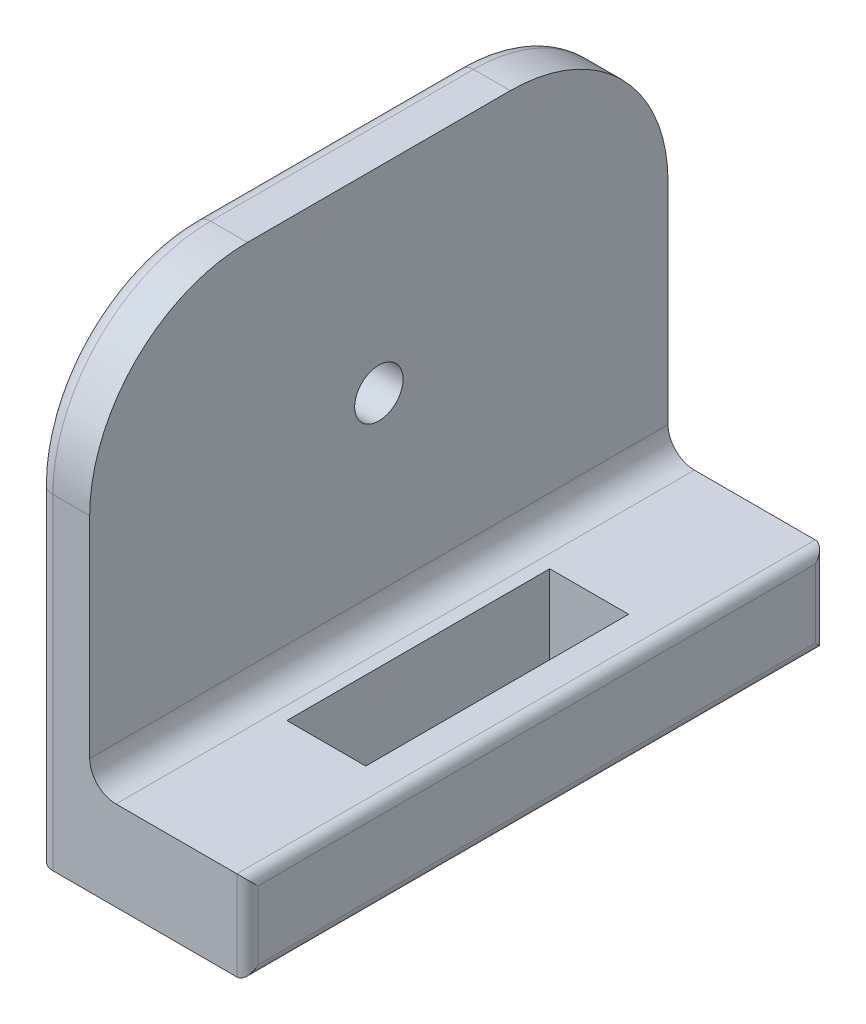
SolidWorks part; units mm, degrees
ref_plane "Front Plane" through (0, 0, 0) normal (0, 0, 1) x (1, 0, 0)
ref_plane "Top Plane" through (0, 0, 0) normal (0, 1, 0) x (1, 0, 0)
ref_plane "Right Plane" through (0, 0, 0) normal (1, 0, 0) x (0, 0, -1)
sketch "Sketch1" plane through (0, 0, 0) normal (0, 1, 0) x (1, 0, 0)
  line L1 (0, 0) -> (40, 0)
  line L2 (0, 0) -> (0, 110)
  line L3 (0, 110) -> (40, 110)
  line L4 (40, 0) -> (40, 110)
  dimension "D1" = 40
  dimension "D2" = 110
extrude "Boss-Extrude1" add sketch "Sketch1" along normal blind 17
sketch "Sketch4" plane through (0, 0, 0) normal (1, 0, 0) x (0, 0, -1)
  line L1 (0, 17) -> (110, 17)
  line L2 (0, 17) -> (0, 92)
  line L3 (0, 92) -> (110, 92)
  line L4 (110, 17) -> (110, 92)
  dimension "D1" = 75
extrude "Boss-Extrude2" add sketch "Sketch4" along normal blind 10
sketch "Sketch5" plane through (0, 17, 0) normal (0, 1, 0) x (1, 0, 0)
  line L0 (25, 0) -> (25, 30) construction
  line L1 (17.5, 80) -> (32.5, 80)
  line L2 (17.5, 80) -> (17.5, 30)
  line L3 (17.5, 30) -> (32.5, 30)
  line L4 (32.5, 80) -> (32.5, 30)
  line L5 (10, 0) -> (40, 0) construction
  line L6 (40, 55) -> (32.5, 55) construction
  line L7 (40, 0) -> (40, 110) construction
  dimension "D1" = 30
  dimension "D2" = 7.5
extrude "Cut-Extrude1" cut sketch "Sketch5" against normal up to surface (17 mm away) up to face at (20, 0, -55)
sketch "Sketch6" plane through (10, 0, 0) normal (1, 0, 0) x (0, 0, -1)
  line L0 (55, 17) -> (55, 54.7) construction
  line L1 (0, 17) -> (110, 17) construction
  circle A0 centre (55, 54.7) radius 4.6
  dimension "D1" = 37.7
extrude "Cut-Extrude2" cut sketch "Sketch6" against normal up to surface (10 mm away) up to face at (0, 46, -55)
fillet "Fillet1" radius 30 2 edges at (5, 92, 0) (5, 92, -110)
fillet "Fillet2" radius 3 5 edges at (0, 83.2132, -8.7868) (0, 92, -55) (0, 83.2132, -101.2132) (0, 31, 0) (0, 31, -110)
fillet "Fillet3" radius 5 1 edges at (10, 17, -55)
fillet "Fillet4" radius 2 4 edges at (40, 8.5, 0) (40, 17, -55) (40, 8.5, -110) (40, 0, -55)
